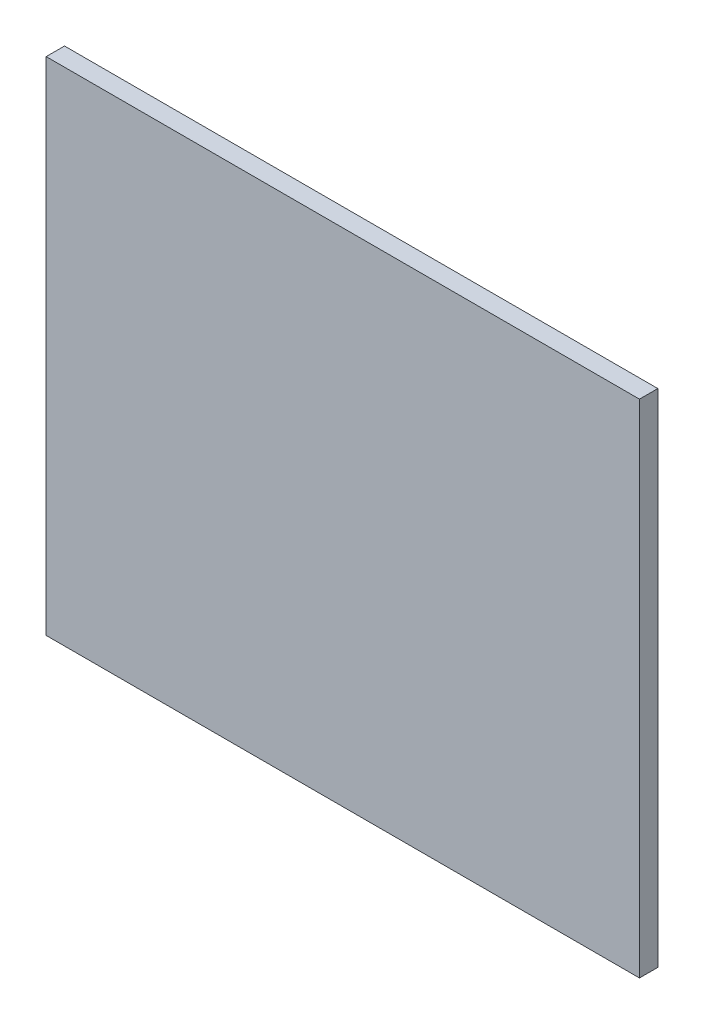
SolidWorks part; units mm, degrees
ref_plane "Plan de face" through (0, 0, 0) normal (0, 0, 1) x (1, 0, 0)
ref_plane "Plan de dessus" through (0, 0, 0) normal (0, 1, 0) x (1, 0, 0)
ref_plane "Plan de droite" through (0, 0, 0) normal (1, 0, 0) x (0, 0, -1)
sketch "Esquisse1" plane through (0, 0, 0) normal (0, 0, 1) x (1, 0, 0)
  line L1 (97, -81.96) -> (-97, -81.96)
  line L2 (97, -81.96) -> (97, 81.96)
  line L3 (97, 81.96) -> (-97, 81.96)
  line L4 (-97, -81.96) -> (-97, 81.96)
  line L5 (97, -81.96) -> (-97, 81.96) construction
  line L6 (97, 81.96) -> (-97, -81.96) construction
  point P0 (0, 0)
extrude "Boss.-Extru.1" add sketch "Esquisse1" along normal blind 6
